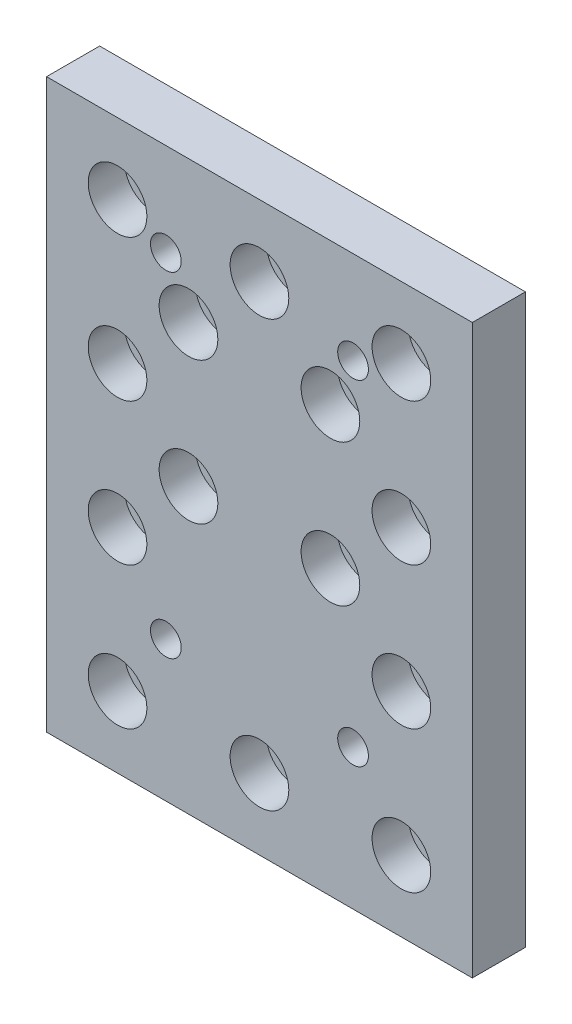
SolidWorks part; units mm, degrees
ref_plane "Front Plane" through (0, 0, 0) normal (0, 0, 1) x (1, 0, 0)
ref_plane "Top Plane" through (0, 0, 0) normal (0, 1, 0) x (1, 0, 0)
ref_plane "Right Plane" through (0, 0, 0) normal (1, 0, 0) x (0, 0, -1)
sketch "Sketch1" plane through (0, 0, 0) normal (0, 0, 1) x (1, 0, 0)
  line L5 (-64.52, -20.9042) -> (11.68, -20.9042)
  line L6 (11.68, -20.9042) -> (11.68, 80.6958)
  line L7 (11.68, 80.6958) -> (-64.52, 80.6958)
  line L8 (-64.52, 80.6958) -> (-64.52, -20.9042)
  line L9 (-64.52, -20.9042) -> (11.68, -20.9042)
  line L10 (11.68, -20.9042) -> (11.68, 80.6958)
  line L11 (11.68, 80.6958) -> (-64.52, 80.6958)
  line L12 (-64.52, 80.6958) -> (-64.52, -20.9042)
  circle A0 centre (-1.02, 17.1958) radius 3.175
  circle A1 centre (-13.72, 29.8958) radius 3.175
  circle A3 centre (-1.02, 42.5958) radius 3.175
  circle A5 centre (-13.72, 55.2958) radius 3.175
  circle A7 centre (-1.02, 67.9958) radius 3.175
  circle A9 centre (-1.02, 17.1958) radius 3.429
  circle A10 centre (-1.02, 17.1958) radius 3.429 construction
  circle A11 centre (-13.72, 29.8958) radius 3.429
  circle A12 centre (-13.72, 29.8958) radius 3.429 construction
  circle A13 centre (-1.02, 42.5958) radius 3.429
  circle A14 centre (-1.02, 42.5958) radius 3.429 construction
  circle A15 centre (-13.72, 55.2958) radius 3.429
  circle A16 centre (-13.72, 55.2958) radius 3.429 construction
  circle A17 centre (-1.02, 67.9958) radius 3.429
  circle A18 centre (-1.02, 67.9958) radius 3.429 construction
  circle A19 centre (-26.42, 67.9958) radius 3.429
  circle A20 centre (-26.42, 67.9958) radius 3.429 construction
  circle A21 centre (-39.12, 55.2958) radius 3.429
  circle A22 centre (-39.12, 55.2958) radius 3.429 construction
  circle A23 centre (-51.82, 67.9958) radius 3.429
  circle A24 centre (-51.82, 67.9958) radius 3.429 construction
  circle A25 centre (-51.82, 42.5958) radius 3.429
  circle A26 centre (-51.82, 42.5958) radius 3.429 construction
  circle A27 centre (-51.82, 17.1958) radius 3.429
  circle A28 centre (-51.82, 17.1958) radius 3.429 construction
  circle A29 centre (-39.12, 29.8958) radius 3.429
  circle A30 centre (-39.12, 29.8958) radius 3.429 construction
  circle A31 centre (-39.12, 4.4958) radius 3.429
  circle A32 centre (-39.12, 4.4958) radius 3.429 construction
  circle A33 centre (-13.72, 4.4958) radius 3.429
  circle A34 centre (-13.72, 4.4958) radius 3.429 construction
  circle A35 centre (-1.02, -8.2042) radius 3.429
  circle A36 centre (-1.02, -8.2042) radius 3.429 construction
  circle A37 centre (-26.42, -8.2042) radius 3.429
  circle A38 centre (-26.42, -8.2042) radius 3.429 construction
  circle A39 centre (-51.82, -8.2042) radius 3.429
  circle A40 centre (-51.82, -8.2042) radius 3.429 construction
  circle A41 centre (-26.42, 67.9958) radius 3.175
  circle A42 centre (-39.12, 55.2958) radius 3.175
  circle A43 centre (-51.82, 67.9958) radius 3.175
  circle A44 centre (-51.82, 42.5958) radius 3.175
  circle A45 centre (-51.82, 17.1958) radius 3.175
  circle A46 centre (-39.12, 29.8958) radius 3.175
  circle A47 centre (-39.12, 4.4958) radius 3.229 construction
  circle A48 centre (-13.72, 4.4958) radius 3.229 construction
  circle A49 centre (-1.02, -8.2042) radius 3.175
  circle A50 centre (-26.42, -8.2042) radius 3.175
  circle A51 centre (-51.82, -8.2042) radius 3.175
  circle A52 centre (-43.17, 4.2072) radius 2.75 construction
  circle A53 centre (-9.67, 4.2072) radius 2.75 construction
  circle A54 centre (-9.67, 64.1072) radius 2.75 construction
  circle A55 centre (-43.17, 64.1072) radius 2.75 construction
  circle A56 centre (-43.17, 4.2072) radius 2.75
  circle A57 centre (-9.67, 4.2072) radius 2.75
  circle A58 centre (-9.67, 64.1072) radius 2.75
  circle A59 centre (-43.17, 64.1072) radius 2.75
  dimension "D3" = 6.35
  dimension "D4" = 0
  dimension "D5" = 0
  dimension "D6" = 0
  dimension "D7" = 0
  dimension "D8" = 0
  dimension "D9" = 0
  dimension "D10" = 0
  dimension "D11" = 0
  dimension "D12" = 0
  dimension "D13" = 0
  dimension "D14" = 0
  dimension "D15" = 0
  dimension "D16" = 0
  dimension "D17" = 0
  dimension "D18" = 0
  dimension "D19" = 0
  dimension "D20" = 0
extrude "Boss-Extrude1" add sketch "Sketch1" along normal blind 9.5
sketch "草图1" plane through (0, 0, 9.5) normal (0, 0, 1) x (1, 0, 0)
  circle A0 centre (-51.82, -8.2042) radius 3.175 construction
  circle A1 centre (-26.42, -8.2042) radius 3.175 construction
  circle A2 centre (-1.02, -8.2042) radius 3.175 construction
  circle A3 centre (-1.02, 17.1958) radius 3.175 construction
  circle A4 centre (-51.82, 17.1958) radius 3.175 construction
  circle A5 centre (-39.12, 29.8958) radius 3.175 construction
  circle A6 centre (-13.72, 29.8958) radius 3.175 construction
  circle A7 centre (-1.02, 42.5958) radius 3.175 construction
  circle A8 centre (-51.82, 42.5958) radius 3.175 construction
  circle A9 centre (-39.12, 55.2958) radius 3.175 construction
  circle A10 centre (-13.72, 55.2958) radius 3.175 construction
  circle A11 centre (-1.02, 67.9958) radius 3.175 construction
  circle A12 centre (-26.42, 67.9958) radius 3.175 construction
  circle A13 centre (-51.82, 67.9958) radius 3.175 construction
  circle A14 centre (-51.82, -8.2042) radius 3.175 construction
  circle A15 centre (-26.42, -8.2042) radius 3.175 construction
  circle A16 centre (-1.02, -8.2042) radius 3.175 construction
  circle A17 centre (-1.02, 17.1958) radius 3.175 construction
  circle A18 centre (-51.82, 17.1958) radius 3.175 construction
  circle A19 centre (-39.12, 29.8958) radius 3.175 construction
  circle A20 centre (-13.72, 29.8958) radius 3.175 construction
  circle A21 centre (-1.02, 42.5958) radius 3.175 construction
  circle A22 centre (-51.82, 42.5958) radius 3.175 construction
  circle A23 centre (-39.12, 55.2958) radius 3.175 construction
  circle A24 centre (-13.72, 55.2958) radius 3.175 construction
  circle A25 centre (-1.02, 67.9958) radius 3.175 construction
  circle A26 centre (-26.42, 67.9958) radius 3.175 construction
  circle A27 centre (-51.82, 67.9958) radius 3.175 construction
  circle A28 centre (-51.82, -8.2042) radius 5.25
  circle A29 centre (-26.42, -8.2042) radius 5.25
  circle A30 centre (-1.02, -8.2042) radius 5.25
  circle A31 centre (-1.02, 17.1958) radius 5.25
  circle A32 centre (-51.82, 17.1958) radius 5.25
  circle A33 centre (-39.12, 29.8958) radius 5.25
  circle A34 centre (-13.72, 29.8958) radius 5.25
  circle A35 centre (-1.02, 42.5958) radius 5.25
  circle A36 centre (-51.82, 42.5958) radius 5.25
  circle A37 centre (-39.12, 55.2958) radius 5.25
  circle A38 centre (-13.72, 55.2958) radius 5.25
  circle A39 centre (-1.02, 67.9958) radius 5.25
  circle A40 centre (-26.42, 67.9958) radius 5.25
  circle A41 centre (-51.82, 67.9958) radius 5.25
  dimension "D1" = 10.5
extrude "切除-拉伸1" cut sketch "草图1" against normal blind 6.5
